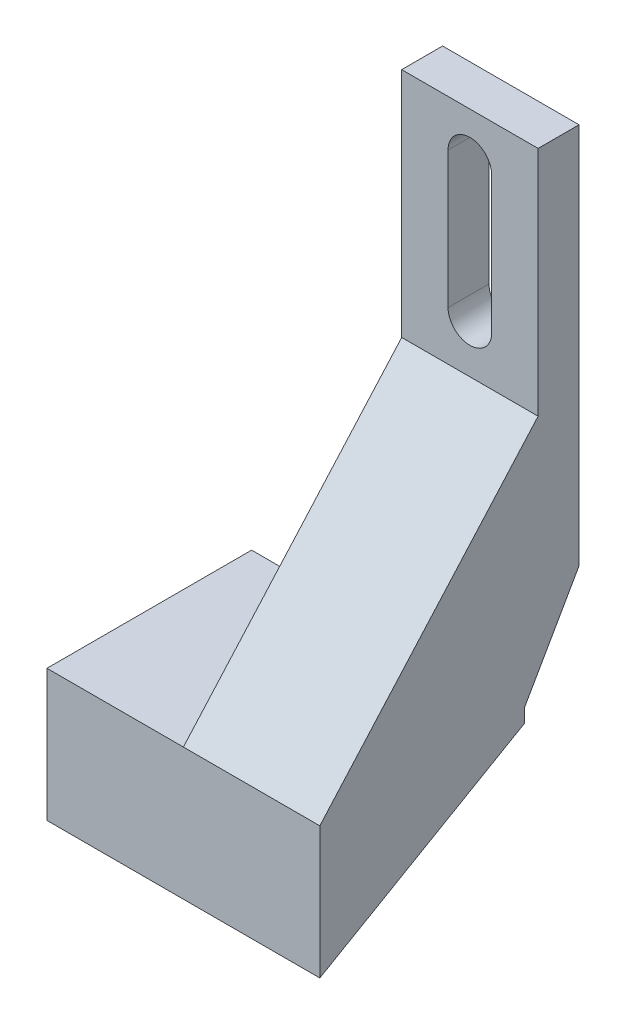
SolidWorks part; units mm, degrees
ref_plane "Front Plane" through (0, 0, 0) normal (0, 0, 1) x (1, 0, 0)
ref_plane "Top Plane" through (0, 0, 0) normal (0, 1, 0) x (1, 0, 0)
ref_plane "Right Plane" through (0, 0, 0) normal (1, 0, 0) x (0, 0, -1)
sketch "Sketch1" plane through (0, 0, 0) normal (0, 0, 1) x (1, 0, 0)
  line L0 (0, 31.6) -> (0, 21.6) construction
  line L1 (-5, 0) -> (5, 0)
  line L2 (-5, 0) -> (-5, 35)
  line L3 (-5, 35) -> (5, 35)
  line L4 (5, 0) -> (5, 35)
  line L5 (1.6, 31.6) -> (1.6, 21.6)
  line L6 (-1.6, 31.6) -> (-1.6, 21.6)
  line L7 (-5, 10) -> (5, 10)
  arc A0 (1.6, 31.6) -> (-1.6, 31.6) centre (0, 31.6) ccw
  arc A1 (-1.6, 21.6) -> (1.6, 21.6) centre (0, 21.6) ccw
  point P4 (0, 0)
  point P8 (0, 26.6)
  dimension "D3" = 1.6
  dimension "D1" = 10
  dimension "D2" = 35
  dimension "D4" = 10
  dimension "D5" = 21.6
  dimension "D6" = 10
extrude "Boss-Extrude1" add sketch "Sketch1" along normal blind 3 contours L2 L7 L4 L3 A1 L6 A0 L5
sketch "Sketch3" plane through (5, 0, 0) normal (1, 0, 0) x (0, 0, -1)
  line L0 (-3, 10) -> (-3, 35) construction
  line L1 (0, 10) -> (-7, 10)
  line L2 (0, 10) -> (0, 7)
  line L3 (0, 7) -> (-7, 7)
  line L4 (-7, 10) -> (-7, 7)
  line L6 (-7, 7) -> (-4, 7)
  line L7 (-7, 7) -> (-7, 0)
  line L8 (-7, 0) -> (-4, 0)
  line L9 (-4, 7) -> (-4, 0)
  line M10 (-3, 10) -> (0, 10)
  dimension "D1" = 4
  dimension "D2" = 3
  dimension "D3" = 7
  dimension "D4" = 3
extrude "Boss-Extrude2" add sketch "Sketch3" against normal blind 10 contours L1 L4 L3 L2 M10 | L9 L3 L7 L8
sketch "Sketch4" plane through (5, 0, 0) normal (1, 0, 0) x (0, 0, -1)
  line L0 (-4, 0) -> (-19, -9.6603)
  line L1 (-19, -9.6603) -> (-19, 0)
  line L2 (-19, 0) -> (-4, 0)
  line L3 (-4, 0) -> (-4, -1)
  line L4 (-4, -1) -> (-19, -9.6603)
  line M9 (-7, 0) -> (-4, 0)
  dimension "D1" = 30
  dimension "D2" = 15
  dimension "D3" = 1
extrude "Boss-Extrude3" add sketch "Sketch4" against normal blind 20 contours L2 L1 L0 M9 | L4 L3 L0
sketch "Sketch5" plane through (-5, 0, 0) normal (-1, 0, 0) x (0, 0, 1)
  line L0 (0, 7) -> (4, 0)
  line L1 (4, 0) -> (4, 7)
  line L2 (4, 7) -> (0, 7)
  line L3 (3, 18) -> (9.0276, 11.2189)
  line L4 (3, 10) -> (3, 35) construction
  line L5 (9.0276, 11.2189) -> (19, 0)
  line L6 (0, 7) -> (3, 18)
  line L7 (19, 0) -> (4, 0)
  line M2 (0, 7) -> (4, 7)
  line M3 (4, 7) -> (4, 0)
  line M4 (4, 0) -> (7, 0)
  line M5 (7, 0) -> (7, 10)
  line M6 (7, 10) -> (3, 10)
  line M7 (3, 10) -> (3, 35)
  dimension "D1" = 2
extrude "Boss-Extrude4" add sketch "Sketch5" against normal up to surface (10 mm away) contours L0 M2 M3 | L6 M2 M3 M4 M5 M6 M7 | L3 M7 M6 | L7 L5 M5 up to face at (5, 9.334, 6.6)
